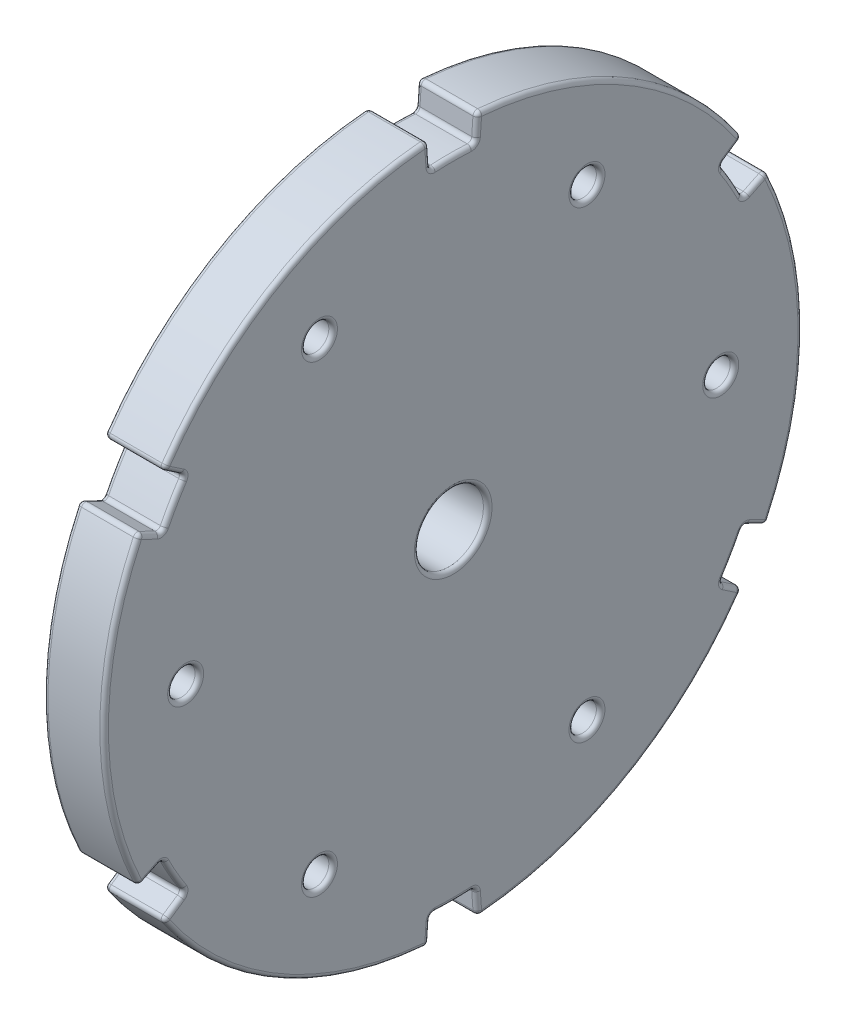
SolidWorks part; units mm, degrees
ref_plane "Front Plane" through (0, 0, 0) normal (0, 0, 1) x (1, 0, 0)
ref_plane "Top Plane" through (0, 0, 0) normal (0, 1, 0) x (1, 0, 0)
ref_plane "Right Plane" through (0, 0, 0) normal (1, 0, 0) x (0, 0, -1)
sketch "Sketch1" plane through (0, 0, 0) normal (0, 0, 1) x (1, 0, 0)
  line L0 (0, 0) -> (84.887, 0) construction
  line L7 (0, 0) -> (0, 40.45)
  line L8 (0, 40.45) -> (7, 40.45)
  line L11 (7, 40.45) -> (7, 0)
  line L12 (7, 0) -> (0, 0)
  dimension "D2" = 7
  dimension "D3" = 80.9
revolve "Revolve1" add sketch "Sketch1" angle 360 about L0
sketch "Sketch2" plane through (7, 0, 0) normal (1, 0, 0) x (0, 0, -1)
  circle A0 centre (0, 0) radius 31 construction
  circle A1 centre (-31, 0) radius 1.5875
  circle A2 centre (-15.5, 26.8468) radius 1.5875
  circle A3 centre (15.5, 26.8468) radius 1.5875
  circle A4 centre (31, 0) radius 1.5875
  circle A5 centre (15.5, -26.8468) radius 1.5875
  circle A6 centre (-15.5, -26.8468) radius 1.5875
  point P18 (0, 0)
  dimension "D1" = 62
  dimension "D2" = 3.175
  dimension "D3" = 6
extrude "Cut-Extrude1" cut sketch "Sketch2" against normal up to next
sketch "Sketch3" plane through (0, 0, 0) normal (1, 0, 0) x (0, 0, -1)
  line L0 (0, 0) -> (15.5, 26.8468) construction
  circle A0 centre (15.5, 26.8468) radius 2.325
  dimension "D1" = 4.65
extrude "Cut-Extrude2" cut sketch "Sketch3" along normal blind 2.8575
pattern_circular "CirPattern1" count 6 over 360 about axis through (0, 0, 0) along (1, 0, 0) of "Cut-Extrude2"
sketch "Sketch4" plane through (7, 0, 0) normal (1, 0, 0) x (0, 0, -1)
  line L1 (3.6373, 0) -> (1.8187, 3.15) construction
  line L2 (1.8187, 3.15) -> (-1.8187, 3.15) construction
  line L3 (-1.8187, 3.15) -> (-3.6373, 0) construction
  line L4 (-3.6373, 0) -> (-1.8187, -3.15) construction
  line L5 (-1.8187, -3.15) -> (1.8187, -3.15) construction
  line L6 (1.8187, -3.15) -> (3.6373, 0) construction
  circle A0 centre (0, 0) radius 4
  circle A1 centre (0, 0) radius 3.15 construction
  dimension "D1" = 6.3
  dimension "D2" = 8
extrude "Cut-Extrude3" cut sketch "Sketch4" against normal up to next
sketch "Sketch5" plane through (7, 0, 0) normal (1, 0, 0) x (0, 0, -1)
  line L0 (0, 0) -> (-2.8216, 40.3515) construction
  line L1 (0, 0) -> (2.8216, 40.3515) construction
  line L4 (0, 45.45) -> (0, 0) construction
  line L5 (-2.8216, 40.3515) -> (-2.6119, 37.3515)
  line L6 (2.8216, 40.3515) -> (2.6119, 37.3515)
  circle A0 centre (0, 0) radius 40.45 construction
  arc A2 (2.8216, 40.3515) -> (-2.8216, 40.3515) centre (0, 0) ccw
  arc A3 (-2.6119, 37.3515) -> (2.6119, 37.3515) centre (0, 0) cw
  point P5 (-3.8413, 36.6807)
  point P9 (0, 37.4427)
  point P10 (2.9305, 40.3437)
  dimension "D1" = 8
  dimension "D2" = 3
extrude "Cut-Extrude4" cut sketch "Sketch5" against normal up to next
pattern_circular "CirPattern2" count 6 over 360 about axis through (0, 0, 0) along (1, 0, 0) of "Cut-Extrude4"
fillet "Fillet1" radius 0.5 88 edges at (2.8575, -26.8468, -17.0875) (2.8575, -26.8468, 13.9125) (2.8575, 0, 29.4125) (2.8575, 26.8468, 13.9125) (2.8575, 26.8468, -17.0875) (2.8575, 0, -32.5875) (0, 0, -4) (7, 0, -4) (7, 26.8468, 13.9125) (7, 26.8468, -17.0875) (7, 0, -32.5875) (7, -26.8468, -17.0875) (7, -26.8468, 13.9125) (7, 0, 29.4125) (0, -2.0135, -32.1625) (0, -28.8603, -14.3375) (0, -26.8468, 17.825) (0, 2.0135, 32.1625) (0, 28.8603, 14.3375) (0, 26.8468, -17.825) (0, 17.073, 35.0047) (0, 0, 40.45) (0, -17.073, 35.0047) (0, -18.7213, 32.4263) (0, -38.8515, 2.7168) (0, -37.4427, 0) (0, -38.8515, -2.7168) (0, -35.0307, -20.225) (0, -21.7785, -32.288) (0, -18.7213, -32.4263) (0, -17.073, -35.0047) (0, 0, -40.45) (0, 18.7213, -32.4263) (0, 21.7785, -32.288) (0, 35.0307, -20.225) (0, 38.8515, -2.7168) (0, 37.4427, 0) (0, 38.8515, 2.7168) (0, 35.0307, 20.225) (0, 21.7785, 32.288) (0, 18.7213, 32.4263) (7, 38.8515, 2.7168) (7, 37.4427, 0) (7, 38.8515, -2.7168) (7, 35.0307, -20.225) (7, 21.7785, -32.288) (7, 18.7213, -32.4263) (7, 17.073, -35.0047) (7, 0, -40.45) (7, -17.073, -35.0047) (7, -18.7213, -32.4263) (7, -21.7785, -32.288) (7, -35.0307, -20.225) (7, -38.8515, -2.7168) (7, -37.4427, 0) (7, -38.8515, 2.7168) (7, -35.0307, 20.225) (7, -21.7785, 32.288) (7, -18.7213, 32.4263) (7, -17.073, 35.0047) (7, 0, 40.45) (7, 17.073, 35.0047) (7, 18.7213, 32.4263) (7, 21.7785, 32.288) (7, 35.0307, 20.225) (3.5, 37.3515, -2.6119) (3.5, 37.3515, 2.6119) (3.5, 20.9377, 31.0414) (3.5, 16.4138, 33.6533) (3.5, -16.4138, 33.6533) (3.5, -20.9377, 31.0414) (3.5, -37.3515, 2.6119) (3.5, -37.3515, -2.6119) (3.5, -20.9377, -31.0414) (3.5, -16.4138, -33.6533) (3.5, 16.4138, -33.6533) (3.5, 20.9377, -31.0414) (3.5, -17.7321, 36.3562) (3.5, 17.7321, 36.3562) (3.5, -40.3515, 2.8216) (3.5, -22.6194, 33.5346) (3.5, -22.6194, -33.5346) (3.5, 17.7321, -36.3562) (3.5, -17.7321, -36.3562) (3.5, 40.3515, 2.8216) (3.5, 22.6194, 33.5346) (3.5, 40.3515, -2.8216) (3.5, 22.6194, -33.5346)
